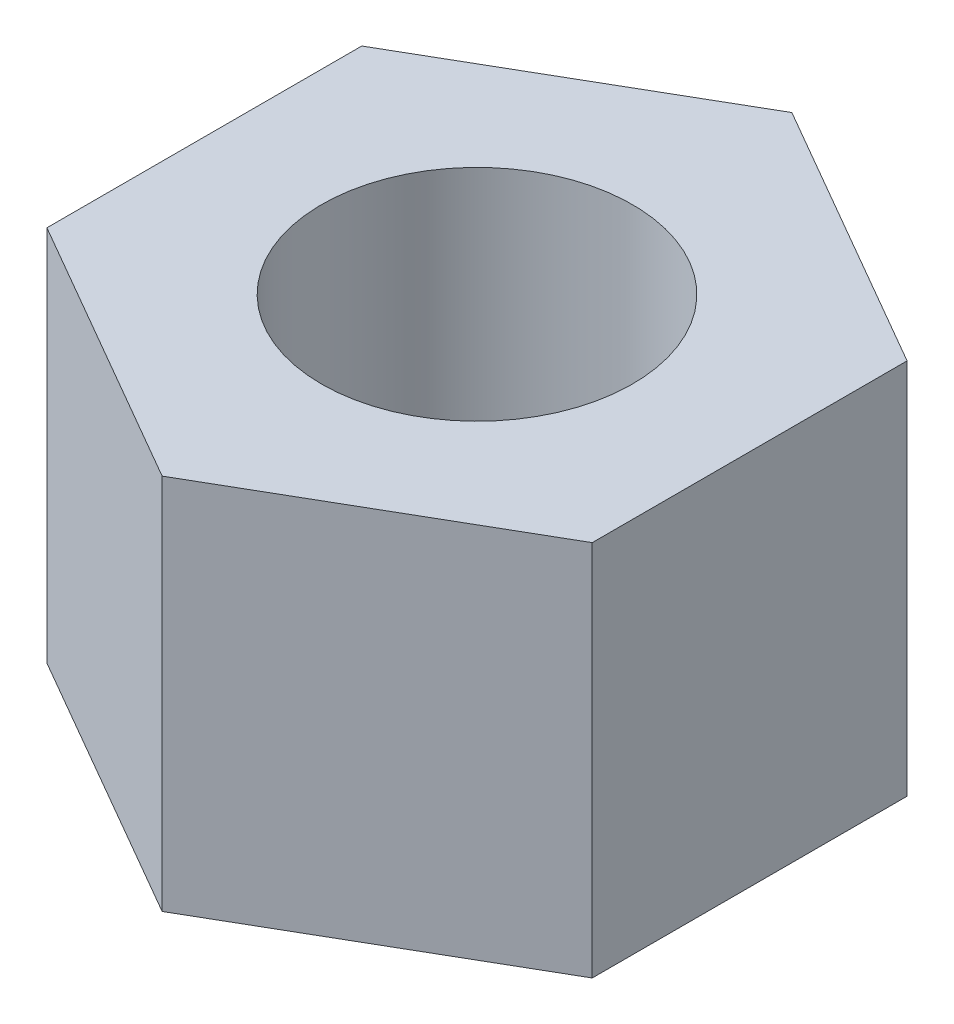
SolidWorks part; units mm, degrees
material "炭素鋼(普通)"
ref_plane "正面" through (0, 0, 0) normal (0, 0, 1) x (1, 0, 0)
ref_plane "平面" through (0, 0, 0) normal (0, 1, 0) x (1, 0, 0)
ref_plane "右側面" through (0, 0, 0) normal (1, 0, 0) x (0, 0, -1)
sketch "ｽｹｯﾁ1" plane through (0, 0, 0) normal (0, 1, 0) x (1, 0, 0)
  line L1 (3.5074, 2.025) -> (0, 4.05)
  line L2 (0, 4.05) -> (-3.5074, 2.025)
  line L3 (-3.5074, 2.025) -> (-3.5074, -2.025)
  line L4 (-3.5074, -2.025) -> (0, -4.05)
  line L5 (0, -4.05) -> (3.5074, -2.025)
  line L6 (3.5074, -2.025) -> (3.5074, 2.025)
  circle A0 centre (0, 0) radius 3.5074 construction
  circle A1 centre (0, 0) radius 2
  dimension "D2" = 4
  dimension "D1" = 8.1
extrude "ﾎﾞｽ - 押し出し1" add sketch "ｽｹｯﾁ1" along normal blind 4.85
